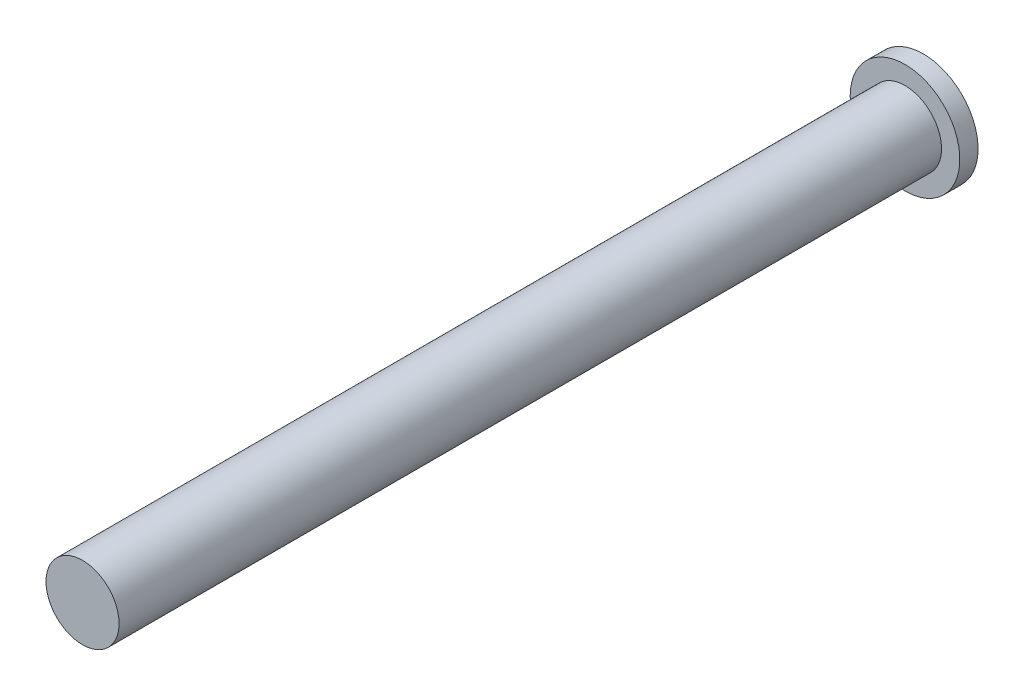
SolidWorks part; units mm, degrees
ref_plane "前视基准面" through (0, 0, 0) normal (0, 0, 1) x (1, 0, 0)
ref_plane "上视基准面" through (0, 0, 0) normal (0, 1, 0) x (1, 0, 0)
ref_plane "右视基准面" through (0, 0, 0) normal (1, 0, 0) x (0, 0, -1)
sketch "草图1" plane through (0, 0, 0) normal (0, 0, 1) x (1, 0, 0)
  circle A0 centre (0, 0) radius 2
  dimension "D1" = 4
extrude "凸台-拉伸1" add sketch "草图1" along normal blind 45
sketch "草图2" plane through (0, 0, 0) normal (0, 0, -1) x (-1, 0, 0)
  circle A0 centre (0, 0) radius 3
  dimension "D1" = 6
extrude "凸台-拉伸2" add sketch "草图2" along normal blind 1
